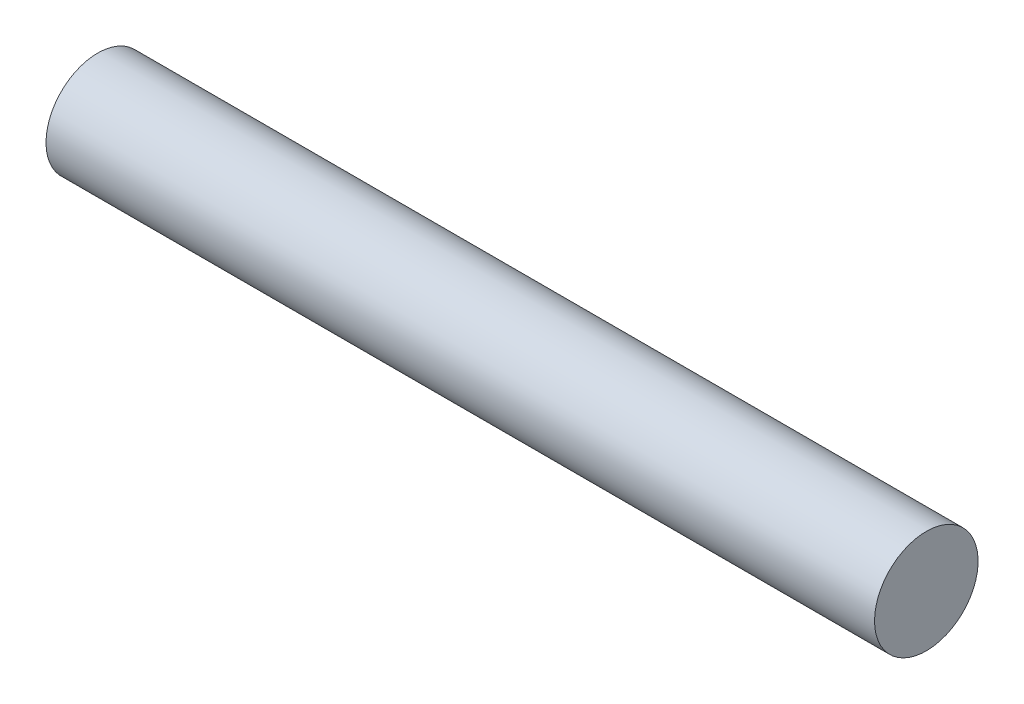
SolidWorks part; units mm, degrees
material "6061 Alloy"
ref_plane "Front Plane" through (0, 0, 0) normal (0, 0, 1) x (1, 0, 0)
ref_plane "Top Plane" through (0, 0, 0) normal (0, 1, 0) x (1, 0, 0)
ref_plane "Right Plane" through (0, 0, 0) normal (1, 0, 0) x (0, 0, -1)
sketch "Croquis1" plane through (0, 0, 0) normal (1, 0, 0) x (0, 0, -1)
  circle A0 centre (0, 0) radius 2.3813
  dimension "D1" = 4.7625
extrude "Saliente-Extruir1" add sketch "Croquis1" along normal mid plane 38.1
